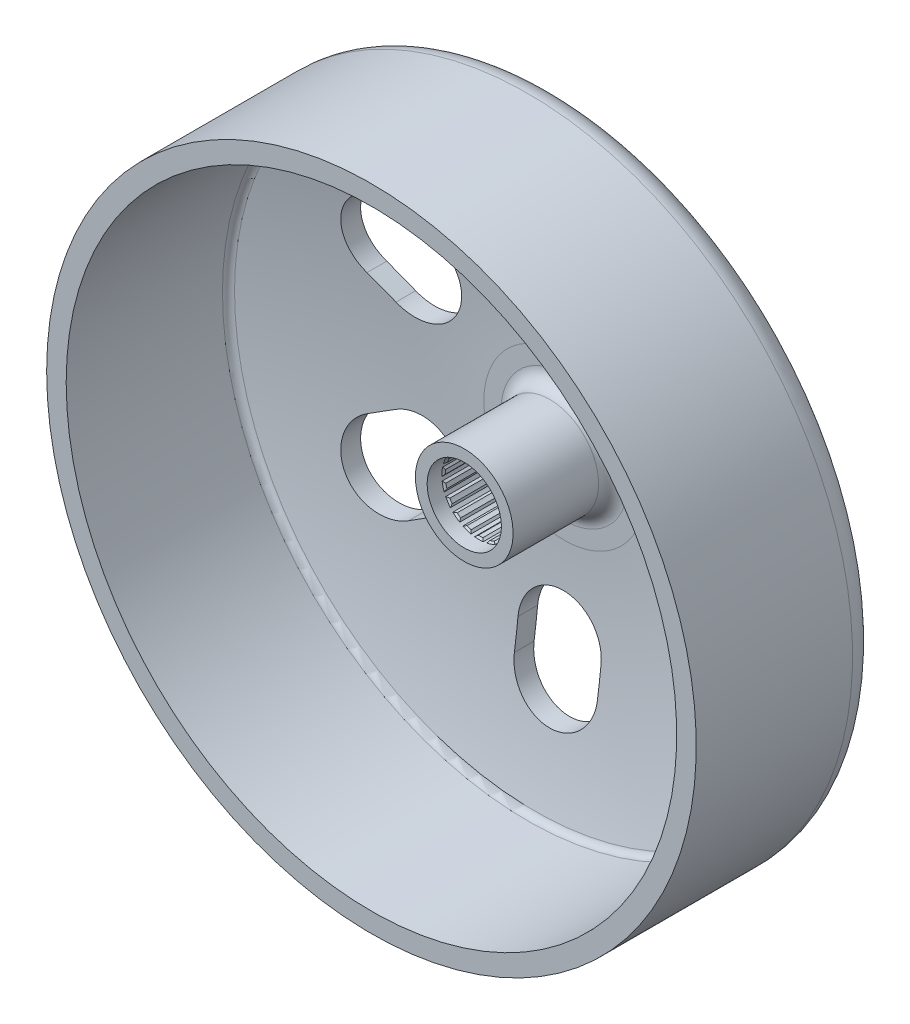
SolidWorks part; units mm, degrees
material "ASTM A36"
ref_plane "Plano frontal" through (0, 0, 0) normal (0, 0, 1) x (1, 0, 0)
ref_plane "Plano superior" through (0, 0, 0) normal (0, 1, 0) x (1, 0, 0)
ref_plane "Plano direito" through (0, 0, 0) normal (1, 0, 0) x (0, 0, -1)
sketch "Esboço1" plane through (0, 0, 0) normal (1, 0, 0) x (0, 0, -1)
  line L0 (0, 0) -> (-12797.7559, 0) construction
  line L1 (0, 9.5) -> (-0.6029, 7.25)
  line L2 (-0.6029, 7.25) -> (-20.65, 7.25)
  line L3 (-20.65, 7.25) -> (-21, 7.6)
  line L4 (-21, 7.6) -> (-24, 7.6)
  line L5 (-24, 7.6) -> (-24, 10)
  line L6 (-24, 10) -> (-6.5, 10)
  line L7 (0, 9.5) -> (0, 6.0087) construction
  line L8 (-3.5, 13) -> (-3.5, 16.5)
  line L9 (0.5, 15.5) -> (0.5, 16.5)
  line L10 (-11, 66.5) -> (-43, 66.5)
  line L11 (-43, 66.5) -> (-43, 62.5)
  line L12 (-11, 62.5) -> (-43, 62.5)
  arc A0 (-6.5, 10) -> (-3.5, 13) centre (-6.5, 13) ccw
  arc A1 (0.5, 16.5) -> (-5.7436, 62.5) centre (-172.0747, 16.5) ccw
  arc A2 (-5.7436, 62.5) -> (-11, 66.5) centre (-11, 61.0463) ccw
  arc A3 (0.5, 15.5) -> (0, 9.5) centre (36.25, 9.5) ccw
  arc A4 (-3.5, 16.5) -> (-9.5989, 61.4338) centre (-172.0747, 16.5) ccw
  arc A5 (-9.5989, 61.4338) -> (-11, 62.5) centre (-11, 61.0463) ccw
  dimension "D12" = 3
  dimension "D15" = 45
  dimension "D1" = 133
  dimension "D2" = 4
  dimension "D3" = 14.5
  dimension "D4" = 15
  dimension "D5" = 3
  dimension "D6" = 19
  dimension "D7" = 31
  dimension "D8" = 0.5
  dimension "D9" = 24
  dimension "D10" = 20
  dimension "D11" = 15.2
  dimension "D13" = 43
  dimension "D14" = 32
  dimension "D16" = 1
revolve "Revolução1" add sketch "Esboço1" angle 360 about L0
sketch "Esboço2" plane through (0, 0, 0) normal (0, 0, 1) x (1, 0, 0)
  line L0 (0, 39.75) -> (0, 33.75) construction
  line L1 (8.5, 39.75) -> (8.5, 33.75)
  line L2 (-8.5, 39.75) -> (-8.5, 33.75)
  line L3 (0, 48.25) -> (0, 25.25) construction
  line L4 (0, 25.25) -> (0, 7.25) construction
  line L5 (-0.3701, 7.591) -> (-0.75, 7.2111)
  line L6 (0.75, 7.2111) -> (0.3701, 7.591)
  line L7 (2.1147, 7.2999) -> (1.6321, 7.0639)
  line L8 (3.0508, 6.5769) -> (2.8149, 7.0595)
  line L9 (4.3704, 6.2177) -> (3.8373, 6.1512)
  line L10 (5.021, 5.2299) -> (4.9546, 5.763)
  line L11 (6.1525, 4.4617) -> (5.6267, 4.572)
  line L12 (6.4471, 3.3162) -> (6.5574, 3.842)
  line L13 (7.2678, 2.2223) -> (6.8063, 2.4973)
  line L14 (7.1746, 1.0432) -> (7.4496, 1.5047)
  line L15 (7.5956, -0.258) -> (7.2484, 0.152)
  line L16 (7.1245, -1.3429) -> (7.5345, -0.9957)
  line L17 (7.1003, -2.7103) -> (6.905, -2.2098)
  line L18 (6.3025, -3.5835) -> (6.8029, -3.3882)
  line L19 (5.8355, -4.8689) -> (5.8133, -4.3322)
  line L20 (4.7974, -5.4357) -> (5.3342, -5.4135)
  line L21 (3.9384, -6.4999) -> (4.0917, -5.985)
  line L22 (2.7725, -6.6989) -> (3.2874, -6.8522)
  line L23 (1.6145, -7.4265) -> (1.9267, -6.9893)
  line L24 (0.4471, -7.2362) -> (0.8844, -7.5484)
  line L25 (-0.8844, -7.5484) -> (-0.4471, -7.2362)
  line L26 (-1.9267, -6.9893) -> (-1.6145, -7.4265)
  line L27 (-3.2874, -6.8522) -> (-2.7725, -6.6989)
  line L28 (-4.0917, -5.985) -> (-3.9384, -6.4999)
  line L29 (-5.3342, -5.4135) -> (-4.7974, -5.4357)
  line L30 (-5.8133, -4.3322) -> (-5.8355, -4.8689)
  line L31 (-6.8029, -3.3882) -> (-6.3025, -3.5835)
  line L32 (-6.905, -2.2098) -> (-7.1003, -2.7103)
  line L33 (-7.5345, -0.9957) -> (-7.1245, -1.3429)
  line L34 (-7.2484, 0.152) -> (-7.5956, -0.258)
  line L35 (-7.4496, 1.5047) -> (-7.1746, 1.0432)
  line L36 (-6.8063, 2.4973) -> (-7.2678, 2.2223)
  line L37 (-6.5574, 3.842) -> (-6.4471, 3.3162)
  line L38 (-5.6267, 4.572) -> (-6.1525, 4.4617)
  line L39 (-4.9546, 5.763) -> (-5.021, 5.2299)
  line L40 (-3.8373, 6.1512) -> (-4.3704, 6.2177)
  line L41 (-2.8149, 7.0595) -> (-3.0508, 6.5769)
  line L42 (-1.6321, 7.0639) -> (-2.1147, 7.2999)
  line L43 (-1.6321, 7.0639) -> (-0.75, 7.2111) construction
  line L44 (-0.75, 7.2111) -> (0.75, 7.2111) construction
  line L45 (34.4245, 19.875) -> (29.2284, 16.875) construction
  line L46 (38.6745, 12.5138) -> (33.4784, 9.5138)
  line L47 (30.1745, 27.2362) -> (24.9784, 24.2362)
  line L48 (34.4245, -19.875) -> (29.2284, -16.875) construction
  line L49 (30.1745, -27.2362) -> (24.9784, -24.2362)
  line L50 (38.6745, -12.5138) -> (33.4784, -9.5138)
  line L51 (0, -39.75) -> (0, -33.75) construction
  line L52 (-8.5, -39.75) -> (-8.5, -33.75)
  line L53 (8.5, -39.75) -> (8.5, -33.75)
  line L54 (-34.4245, -19.875) -> (-29.2284, -16.875) construction
  line L55 (-38.6745, -12.5138) -> (-33.4784, -9.5138)
  line L56 (-30.1745, -27.2362) -> (-24.9784, -24.2362)
  line L57 (-34.4245, 19.875) -> (-29.2284, 16.875) construction
  line L58 (-30.1745, 27.2362) -> (-24.9784, 24.2362)
  line L59 (-38.6745, 12.5138) -> (-33.4784, 9.5138)
  arc A0 (8.5, 39.75) -> (-8.5, 39.75) centre (0, 39.75) ccw
  arc A1 (-8.5, 33.75) -> (8.5, 33.75) centre (0, 33.75) ccw
  circle A2 centre (0, 0) radius 7.25 construction
  circle A3 centre (0, 0) radius 7.6 construction
  arc A4 (0.75, 7.2111) -> (-0.75, 7.2111) centre (0, 0) ccw
  arc A5 (0.3701, 7.591) -> (-0.3701, 7.591) centre (0, 0) ccw
  arc A6 (3.0508, 6.5769) -> (1.6321, 7.0639) centre (0, 0) ccw
  arc A7 (2.8149, 7.0595) -> (2.1147, 7.2999) centre (0, 0) ccw
  arc A8 (5.021, 5.2299) -> (3.8373, 6.1512) centre (0, 0) ccw
  arc A9 (4.9546, 5.763) -> (4.3704, 6.2177) centre (0, 0) ccw
  arc A10 (6.4471, 3.3162) -> (5.6267, 4.572) centre (0, 0) ccw
  arc A11 (6.5574, 3.842) -> (6.1525, 4.4617) centre (0, 0) ccw
  arc A12 (7.1746, 1.0432) -> (6.8063, 2.4973) centre (0, 0) ccw
  arc A13 (7.4496, 1.5047) -> (7.2678, 2.2223) centre (0, 0) ccw
  arc A14 (7.1245, -1.3429) -> (7.2484, 0.152) centre (0, 0) ccw
  arc A15 (7.5345, -0.9957) -> (7.5956, -0.258) centre (0, 0) ccw
  arc A16 (6.3025, -3.5835) -> (6.905, -2.2098) centre (0, 0) ccw
  arc A17 (6.8029, -3.3882) -> (7.1003, -2.7103) centre (0, 0) ccw
  arc A18 (4.7974, -5.4357) -> (5.8133, -4.3322) centre (0, 0) ccw
  arc A19 (5.3342, -5.4135) -> (5.8355, -4.8689) centre (0, 0) ccw
  arc A20 (2.7725, -6.6989) -> (4.0917, -5.985) centre (0, 0) ccw
  arc A21 (3.2874, -6.8522) -> (3.9384, -6.4999) centre (0, 0) ccw
  arc A22 (0.4471, -7.2362) -> (1.9267, -6.9893) centre (0, 0) ccw
  arc A23 (0.8844, -7.5484) -> (1.6145, -7.4265) centre (0, 0) ccw
  arc A24 (-1.9267, -6.9893) -> (-0.4471, -7.2362) centre (0, 0) ccw
  arc A25 (-1.6145, -7.4265) -> (-0.8844, -7.5484) centre (0, 0) ccw
  arc A26 (-4.0917, -5.985) -> (-2.7725, -6.6989) centre (0, 0) ccw
  arc A27 (-3.9384, -6.4999) -> (-3.2874, -6.8522) centre (0, 0) ccw
  arc A28 (-5.8133, -4.3322) -> (-4.7974, -5.4357) centre (0, 0) ccw
  arc A29 (-5.8355, -4.8689) -> (-5.3342, -5.4135) centre (0, 0) ccw
  arc A30 (-6.905, -2.2098) -> (-6.3025, -3.5835) centre (0, 0) ccw
  arc A31 (-7.1003, -2.7103) -> (-6.8029, -3.3882) centre (0, 0) ccw
  arc A32 (-7.2484, 0.152) -> (-7.1245, -1.3429) centre (0, 0) ccw
  arc A33 (-7.5956, -0.258) -> (-7.5345, -0.9957) centre (0, 0) ccw
  arc A34 (-6.8063, 2.4973) -> (-7.1746, 1.0432) centre (0, 0) ccw
  arc A35 (-7.2678, 2.2223) -> (-7.4496, 1.5047) centre (0, 0) ccw
  arc A36 (-5.6267, 4.572) -> (-6.4471, 3.3162) centre (0, 0) ccw
  arc A37 (-6.1525, 4.4617) -> (-6.5574, 3.842) centre (0, 0) ccw
  arc A38 (-3.8373, 6.1512) -> (-5.021, 5.2299) centre (0, 0) ccw
  arc A39 (-4.3704, 6.2177) -> (-4.9546, 5.763) centre (0, 0) ccw
  arc A40 (-1.6321, 7.0639) -> (-3.0508, 6.5769) centre (0, 0) ccw
  arc A41 (-2.1147, 7.2999) -> (-2.8149, 7.0595) centre (0, 0) ccw
  arc A42 (38.6745, 12.5138) -> (30.1745, 27.2362) centre (34.4245, 19.875) ccw
  arc A43 (24.9784, 24.2362) -> (33.4784, 9.5138) centre (29.2284, 16.875) ccw
  arc A44 (30.1745, -27.2362) -> (38.6745, -12.5138) centre (34.4245, -19.875) ccw
  arc A45 (33.4784, -9.5138) -> (24.9784, -24.2362) centre (29.2284, -16.875) ccw
  arc A46 (-8.5, -39.75) -> (8.5, -39.75) centre (0, -39.75) ccw
  arc A47 (8.5, -33.75) -> (-8.5, -33.75) centre (0, -33.75) ccw
  arc A48 (-38.6745, -12.5138) -> (-30.1745, -27.2362) centre (-34.4245, -19.875) ccw
  arc A49 (-24.9784, -24.2362) -> (-33.4784, -9.5138) centre (-29.2284, -16.875) ccw
  arc A50 (-30.1745, 27.2362) -> (-38.6745, 12.5138) centre (-34.4245, 19.875) ccw
  arc A51 (-33.4784, 9.5138) -> (-24.9784, 24.2362) centre (-29.2284, 16.875) ccw
  point P3 (0, 36.75)
  point P12 (0, 7.6)
  point P94 (0, 0)
  point P97 (31.8264, 18.375)
  point P104 (31.8264, -18.375)
  point P111 (0, -36.75)
  point P118 (-31.8264, -18.375)
  point P125 (-31.8264, 18.375)
  point P130 (0, 0)
  dimension "D1" = 17
  dimension "D2" = 18
  dimension "D3" = 23
  dimension "D4" = 1.5
  dimension "D5" = 19
  dimension "D6" = 6
extrude "Corte-extrusão1" cut sketch "Esboço2" against normal through all both and the other way through all
